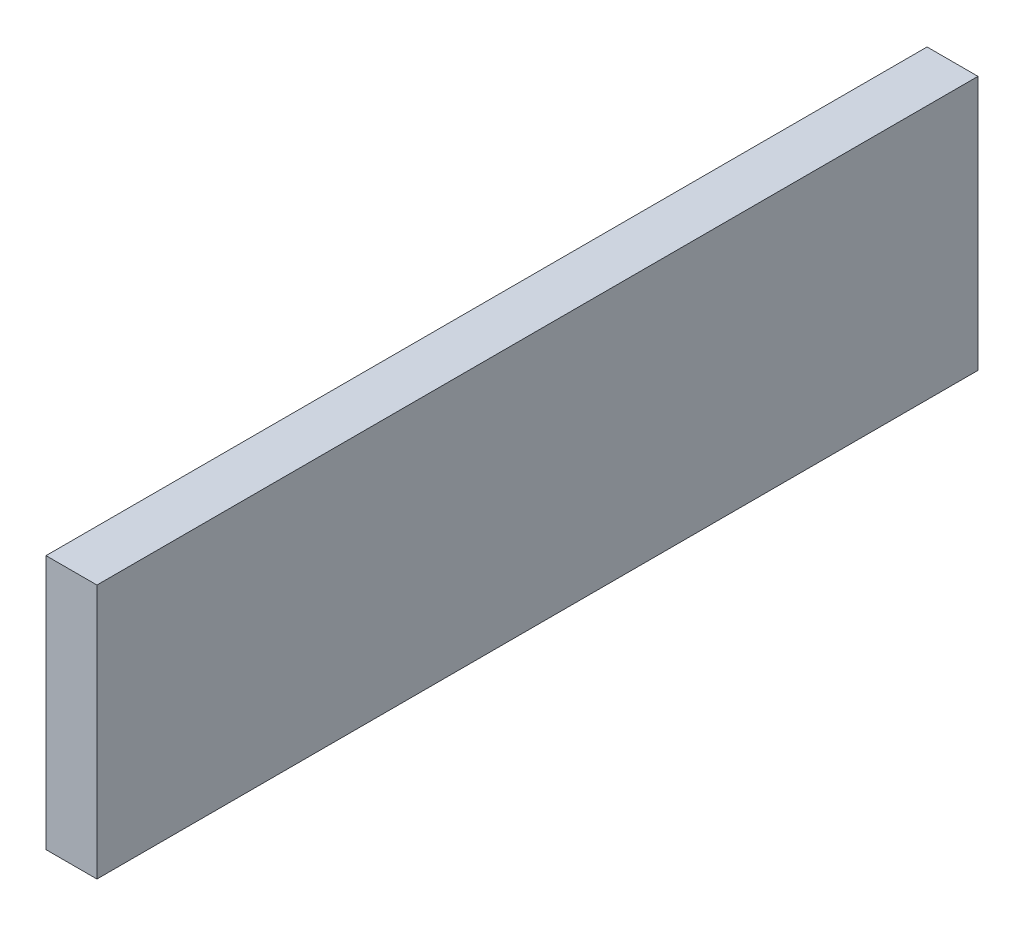
SolidWorks part; units mm, degrees
ref_plane "前视基准面" through (0, 0, 0) normal (0, 0, 1) x (1, 0, 0)
ref_plane "上视基准面" through (0, 0, 0) normal (0, 1, 0) x (1, 0, 0)
ref_plane "右视基准面" through (0, 0, 0) normal (1, 0, 0) x (0, 0, -1)
sketch "草图1" plane through (0, 0, 0) normal (0, 1, 0) x (1, 0, 0)
  line L1 (0, 0) -> (20, 0)
  line L2 (0, 0) -> (0, -346)
  line L3 (0, -346) -> (20, -346)
  line L4 (20, 0) -> (20, -346)
  dimension "D1" = 346
  dimension "D2" = 20
extrude "凸台-拉伸1" add sketch "草图1" along normal blind 100
